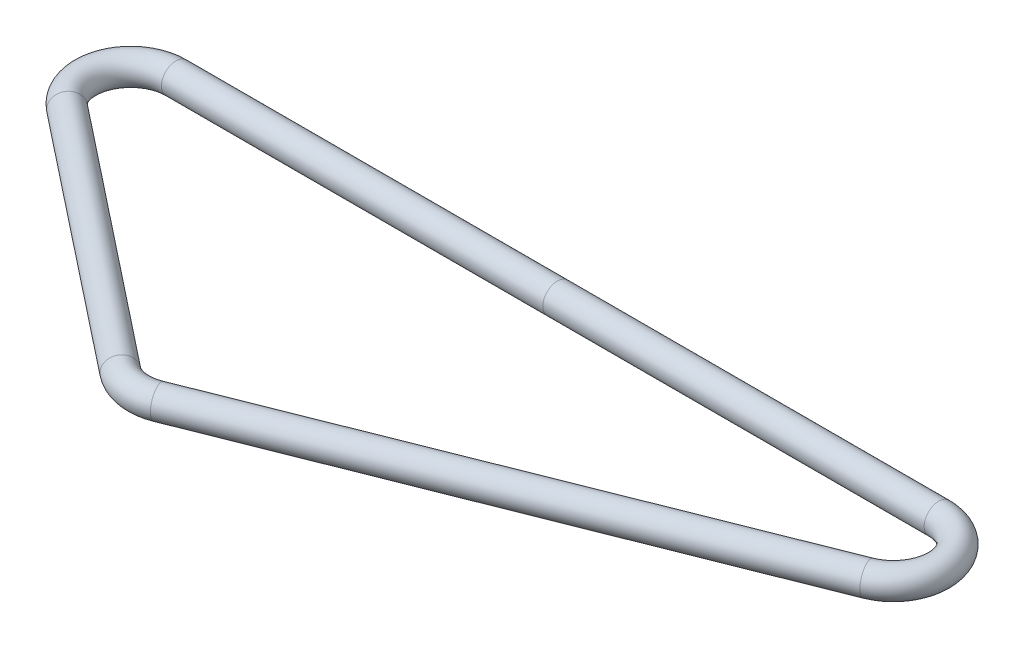
SolidWorks part; units mm, degrees
material "Plain Carbon Steel"
ref_plane "Front Plane" through (0, 0, 0) normal (0, 0, 1) x (1, 0, 0)
ref_plane "Top Plane" through (0, 0, 0) normal (0, 1, 0) x (1, 0, 0)
ref_plane "Right Plane" through (0, 0, 0) normal (1, 0, 0) x (0, 0, -1)
sketch "Sketch4" plane through (0, 0, 0) normal (0, 1, 0) x (1, 0, 0)
  line L9 (-16.5805, -43.6683) -> (60.1431, -13.2053)
  line L10 (-61.8635, -12.212) -> (-23.3522, -42.675)
  line L11 (57.6174, 0) -> (-57.6174, 0)
  arc A9 (60.1431, -13.2053) -> (57.6174, 0) centre (57.6174, -6.8442) ccw
  arc A10 (-23.3522, -42.675) -> (-16.5805, -43.6683) centre (-19.1061, -37.3072) ccw
  arc A11 (-57.6174, 0) -> (-61.8635, -12.212) centre (-57.6174, -6.8442) ccw
  point P1 (0, 0)
  dimension "D5" = 6.8442
  dimension "D6" = 6.8442
  dimension "D7" = 6.8442
  dimension "D2" = 82.55
  dimension "D3" = 49.1031
  dimension "D4" = 115.2349
sketch "Sketch5" plane through (0, 0, 0) normal (1, 0, 0) x (0, 0, -1)
  circle A0 centre (0, 0) radius 2.2034
  dimension "D1" = 4.4069
sweep "Sweep1" add profiles "Sketch5" path "Sketch4"
ref_plane "Plane1" through (13.5325, 0, 34.0828) normal (0.369, 0, 0.9294) x (0.9294, 0, -0.369)
